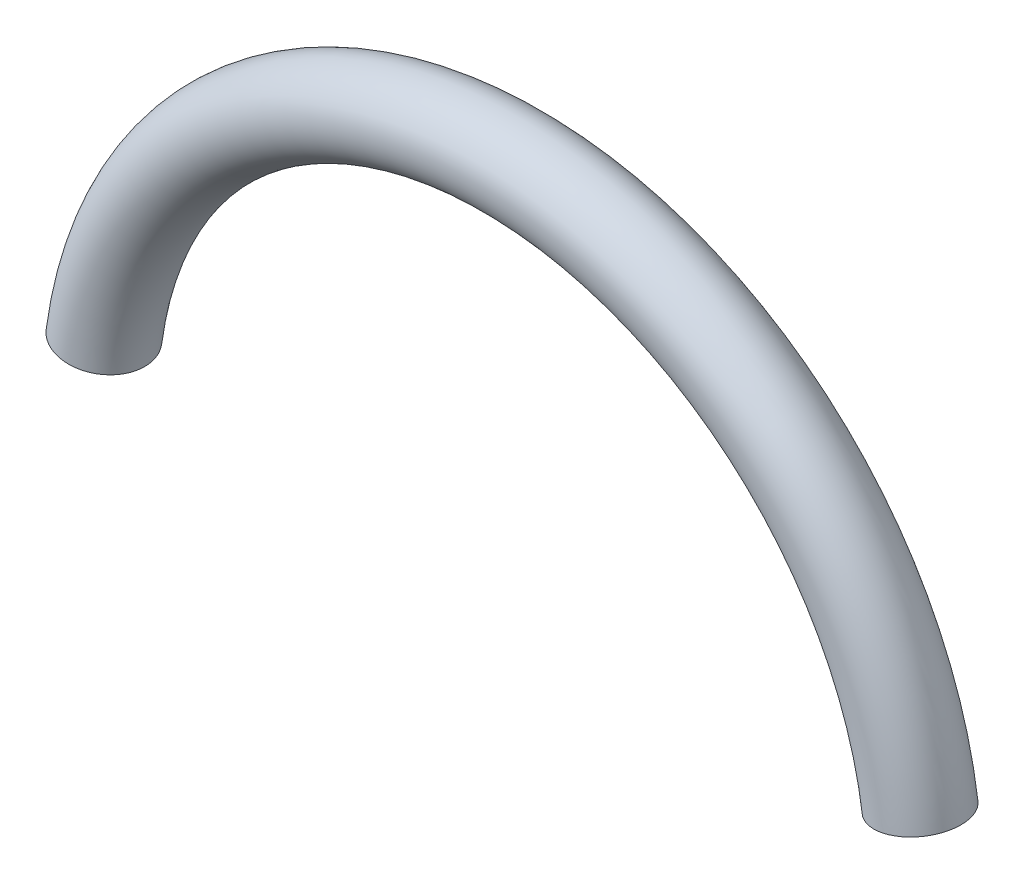
SolidWorks part; units mm, degrees
material "Custom Plastic"
ref_plane "X-Y Datum" through (0, 0, 0) normal (0, 0, 1) x (1, 0, 0)
ref_plane "X-Z Datum" through (0, 0, 0) normal (0, 1, 0) x (1, 0, 0)
ref_plane "Y-Z Datum" through (0, 0, 0) normal (1, 0, 0) x (0, 0, -1)
sketch3d "3DSketch2"
  arc A0 (-76.8626, 112.559, 219.825) -> (-13.9514, 112.559, 219.825) centre (-45.407, 108.2455, 219.825) cw
  circle A1 centre (-76.8626, 112.559, 219.825) radius 4.5 construction
  circle A2 centre (-13.9514, 112.559, 219.825) radius 4.5 construction
  point P2 (-45.407, 108.2455, 188.075)
  point P7 (-74.6126, 116.4561, 219.825)
  point P10 (-16.2014, 116.4561, 219.825)
  dimension "D1" = 31.75
sweep "Sweep1" add path "3DSketch2" circular profile diameter 6.35 parameters "D3"=6.35
